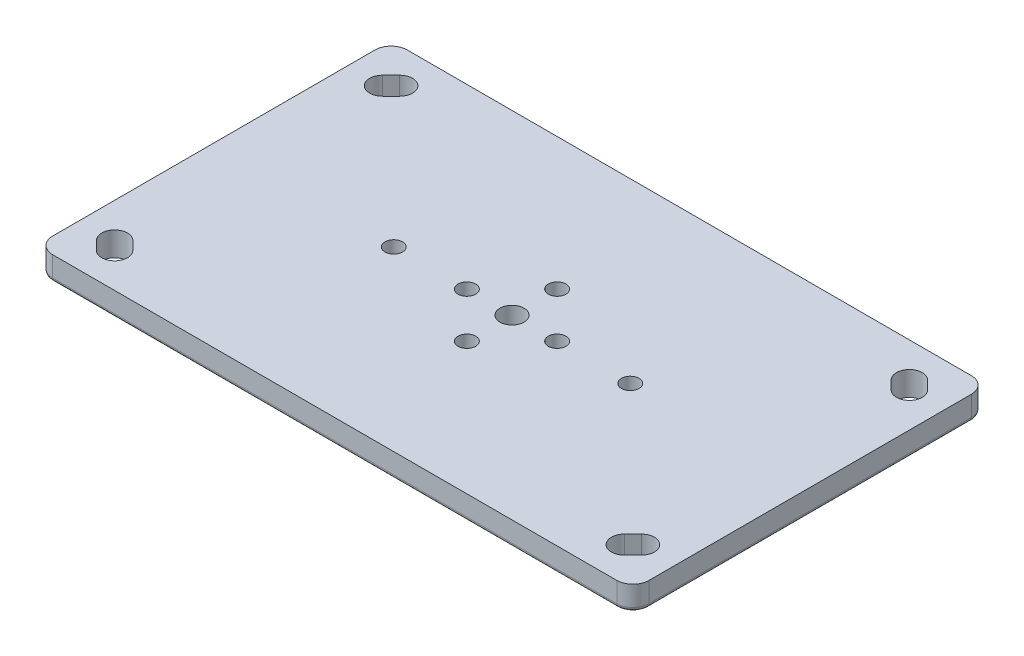
SolidWorks part; units mm, degrees
ref_plane "Front Plane" through (0, 0, 0) normal (0, 0, 1) x (1, 0, 0)
ref_plane "Top Plane" through (0, 0, 0) normal (0, 1, 0) x (1, 0, 0)
ref_plane "Right Plane" through (0, 0, 0) normal (1, 0, 0) x (0, 0, -1)
sketch "Sketch1" plane through (0, 0, 0) normal (0, 1, 0) x (1, 0, 0)
  line L0 (41.5101, 21.1131) -> (40.1631, 22.4601) construction
  line L1 (-46.99, -27.94) -> (46.99, -27.94)
  line L2 (-46.99, -27.94) -> (-46.99, 27.94)
  line L3 (-46.99, 27.94) -> (46.99, 27.94)
  line L4 (46.99, -27.94) -> (46.99, 27.94)
  line L5 (-46.99, -27.94) -> (46.99, 27.94) construction
  line L6 (-46.99, 27.94) -> (46.99, -27.94) construction
  line L7 (40.0733, 19.6763) -> (38.7263, 21.0233)
  line L8 (42.947, 22.5499) -> (41.5999, 23.897)
  line L9 (40.8366, 21.7866) -> (40.8366, 27.94) construction
  line L10 (40.8366, 21.7866) -> (46.99, 21.7866) construction
  line L11 (0, 0) -> (0, 45.8412) construction
  line L12 (0, 0) -> (73.1732, 0) construction
  line L13 (-41.5101, 21.1131) -> (-40.1631, 22.4601) construction
  line L14 (-40.0733, 19.6763) -> (-38.7263, 21.0233)
  line L15 (-42.947, 22.5499) -> (-41.5999, 23.897)
  line L16 (41.5101, -21.1131) -> (40.1631, -22.4601) construction
  line L17 (40.0733, -19.6763) -> (38.7263, -21.0233)
  line L18 (42.947, -22.5499) -> (41.5999, -23.897)
  line L19 (-41.5101, -21.1131) -> (-40.1631, -22.4601) construction
  line L20 (-40.0733, -19.6763) -> (-38.7263, -21.0233)
  line L21 (-42.947, -22.5499) -> (-41.5999, -23.897)
  arc A0 (40.0733, 19.6763) -> (42.947, 22.5499) centre (41.5101, 21.1131) ccw
  arc A1 (41.5999, 23.897) -> (38.7263, 21.0233) centre (40.1631, 22.4601) ccw
  arc A2 (-40.0733, 19.6763) -> (-42.947, 22.5499) centre (-41.5101, 21.1131) cw
  arc A3 (-41.5999, 23.897) -> (-38.7263, 21.0233) centre (-40.1631, 22.4601) cw
  arc A4 (40.0733, -19.6763) -> (42.947, -22.5499) centre (41.5101, -21.1131) cw
  arc A5 (41.5999, -23.897) -> (38.7263, -21.0233) centre (40.1631, -22.4601) cw
  arc A6 (-40.0733, -19.6763) -> (-42.947, -22.5499) centre (-41.5101, -21.1131) ccw
  arc A7 (-41.5999, -23.897) -> (-38.7263, -21.0233) centre (-40.1631, -22.4601) ccw
  circle A8 centre (0, 0) radius 1.905
  point P0 (0, 0)
  point P8 (40.8366, 21.7866)
  point P21 (-40.8366, 21.7866)
  point P28 (40.8366, -21.7866)
  point P35 (-40.8366, -21.7866)
  dimension "D4" = 2.032
  dimension "D7" = 3.81
  dimension "D1" = 93.98
  dimension "D2" = 55.88
  dimension "D3" = 1.905
  dimension "D5" = 45
  dimension "D6" = 8.7022
extrude "Boss-Extrude1" add sketch "Sketch1" along normal blind 3.81 contours L3 L4 L1 L2 | L20 A7 L21 A6 | L14 A3 L15 A2 | L17 A5 L18 A4 | L8 A1 L7 A0 | A8
hole_wizard "7/64 (0.10938) Diameter Hole1" positions "Sketch2" profile "Sketch3" hole size "7/64" standard "ANSI Inch" end condition through all
sketch "Sketch2" plane through (0, 0, 0) normal (0, -1, 0) x (-1, 0, 0)
  point P0 (-18.6309, 0)
  point P3 (0, 7.112)
  point P6 (-7.112, 0)
  point P9 (7.112, 0)
  point P12 (18.6309, 0)
  point P15 (0, -7.112)
sketch "Sketch3" plane through (18.6309, 0, 0) normal (1, 0, 0) x (0, 0, -1)
  line L0 (0, 0) -> (0, 3.81)
  line L1 (0, 3.81) -> (1.3891, 3.81)
  line L2 (1.3891, 3.81) -> (1.3891, 0)
  line L5 (1.3891, 0) -> (0, 0)
  line L11 (0, -6.35) -> (0, 107.95) construction
  dimension "Thru Hole Dia." = 2.7783
  dimension "Thru Hole Depth" = 3.81
fillet "Fillet1" radius 2.54 4 edges at (-46.99, 1.905, -27.94) (-46.99, 1.905, 27.94) (46.99, 1.905, -27.94) (46.99, 1.905, 27.94)
sketch "Sketch4" plane through (0, 0, 0) normal (0, 1, 0) x (1, 0, 0)
  line L1 (-27.94, -22.86) -> (27.94, -22.86)
  line L2 (-40.64, -10.16) -> (-40.64, 10.16)
  line L3 (-27.94, 22.86) -> (27.94, 22.86)
  line L4 (40.64, -10.16) -> (40.64, 10.16)
  line L5 (-40.64, -22.86) -> (40.64, 22.86) construction
  line L6 (-40.64, 22.86) -> (40.64, -22.86) construction
  arc A0 (-27.94, -22.86) -> (-40.64, -10.16) centre (-27.94, -10.16) cw
  arc A1 (27.94, -22.86) -> (40.64, -10.16) centre (27.94, -10.16) ccw
  arc A2 (27.94, 22.86) -> (40.64, 10.16) centre (27.94, 10.16) cw
  arc A3 (-40.64, 10.16) -> (-27.94, 22.86) centre (-27.94, 10.16) cw
  point P0 (0, 0)
  dimension "D3" = 12.7
  dimension "D1" = 45.72
  dimension "D2" = 81.28
extrude "Extrude-Thin1" add sketch "Sketch4" against normal blind 3.81 thin thin type one direction reverse wall 3.81
fillet "Fillet2" radius 1.27 16 edges at (34.2262, -3.81, 16.4462) (36.83, -3.81, 0) (34.2262, -3.81, -16.4462) (0, -3.81, -19.05) (-34.2262, -3.81, -16.4462) (-36.83, -3.81, 0) (-34.2262, -3.81, 16.4462) (0, -3.81, 19.05) (-40.64, -3.81, 0) (-36.9203, -3.81, -19.1403) (0, -3.81, -22.86) (36.9203, -3.81, -19.1403) (40.64, -3.81, 0) (36.9203, -3.81, 19.1403) (0, -3.81, 22.86) (-36.9203, -3.81, 19.1403)
fillet "Fillet3" radius 0.635 16 edges at (-46.2461, 0, 27.1961) (0, 0, 27.94) (46.2461, 0, 27.1961) (46.99, 0, 0) (46.2461, 0, -27.1961) (0, 0, -27.94) (-46.2461, 0, -27.1961) (-36.9203, 0, -19.1403) (0, 0, -22.86) (36.9203, 0, -19.1403) (40.64, 0, 0) (36.9203, 0, 19.1403) (0, 0, 22.86) (-36.9203, 0, 19.1403) (-46.99, 0, 0) (-40.64, 0, 0)
